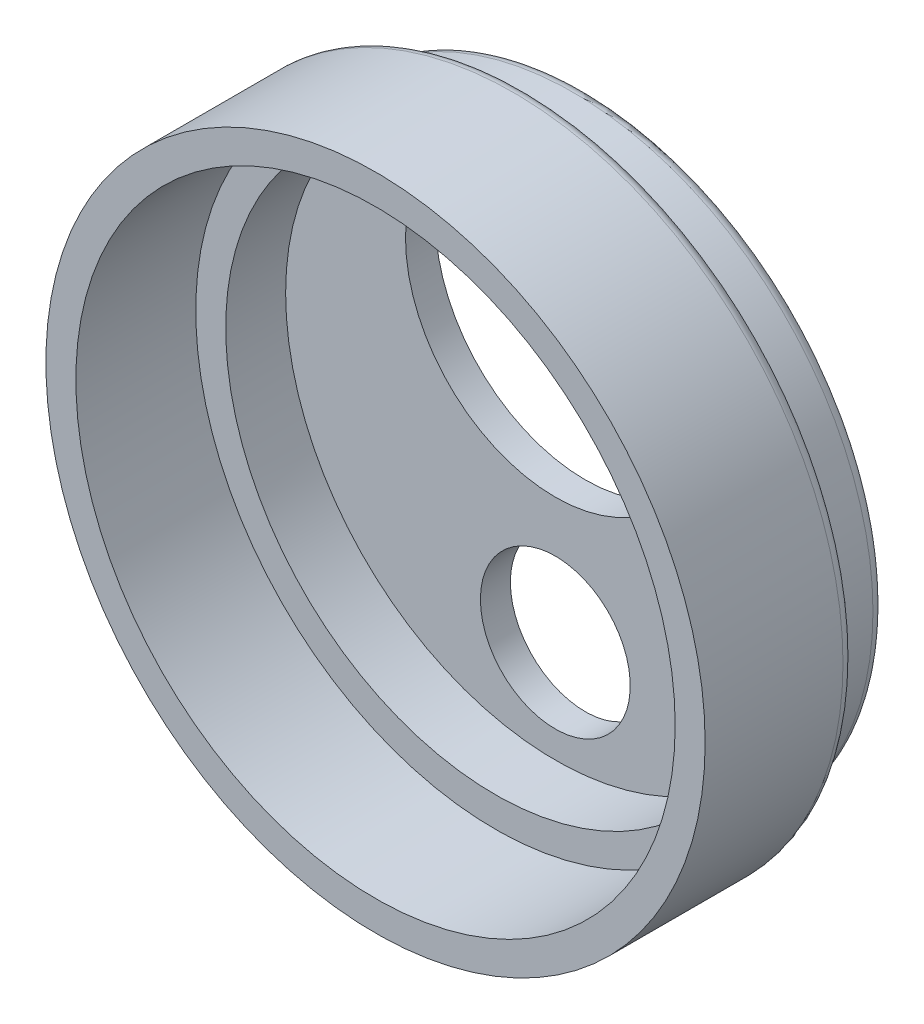
SolidWorks part; units mm, degrees
material "PVC Rígido"
ref_plane "Plano frontal" through (0, 0, 0) normal (0, 0, 1) x (1, 0, 0)
ref_plane "Plano superior" through (0, 0, 0) normal (0, 1, 0) x (1, 0, 0)
ref_plane "Plano direito" through (0, 0, 0) normal (1, 0, 0) x (0, 0, -1)
sketch "Esboço1" plane through (0, 0, 0) normal (0, 0, 1) x (1, 0, 0)
  circle A0 centre (0, 0) radius 55
  dimension "D1" = 110
extrude "Ressalto-extrusão1" add sketch "Esboço1" along normal blind 25 contours A0
sketch "Esboço2" plane through (0, 0, 0) normal (0, 0, -1) x (-1, 0, 0)
  circle A0 centre (0, 0) radius 50
extrude "Ressalto-extrusão2" add sketch "Esboço2" along normal blind 10
shell "Casca1" thickness 5
fillet "Filete2" radius 2 2 edges at (-50, 0, 0) (-50, 0, -10)
fillet "Filete3" radius 2 1 edges at (55, 0, 0)
sketch "Esboço3" plane through (0, 0, -10) normal (0, 0, -1) x (-1, 0, 0)
  line L0 (0, 48) -> (0, -48) construction
  line L1 (0, 0) -> (0, 48) construction
  circle A0 centre (0, 0) radius 48 construction
  circle A1 centre (0, 18) radius 25
  circle A2 centre (0, -28) radius 12.5
  dimension "D1" = 50
  dimension "D3" = 25
  dimension "D2" = 30
  dimension "D4" = 20
extrude "Corte-extrusão1" cut sketch "Esboço3" against normal through all
